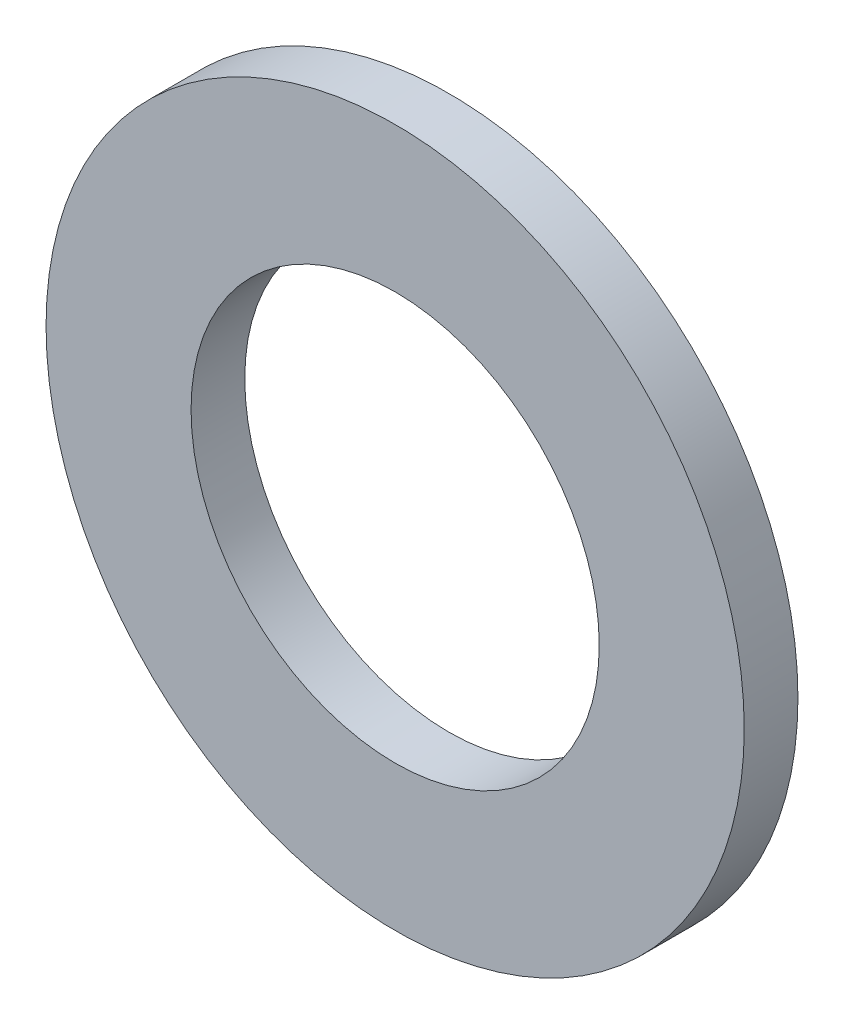
SolidWorks part; units mm, degrees
ref_plane "Спереди" through (0, 0, 0) normal (0, 0, 1) x (1, 0, 0)
ref_plane "Сверху" through (0, 0, 0) normal (0, 1, 0) x (1, 0, 0)
ref_plane "Справа" through (0, 0, 0) normal (1, 0, 0) x (0, 0, -1)
sketch "Эскиз1" plane through (0, 0, 0) normal (0, 0, 1) x (1, 0, 0)
  circle A0 centre (0, 0) radius 19
  circle A1 centre (0, 0) radius 32.5
  dimension "D1" = 38
  dimension "D2" = 65
extrude "Вытянуть1" add sketch "Эскиз1" along normal blind 5
